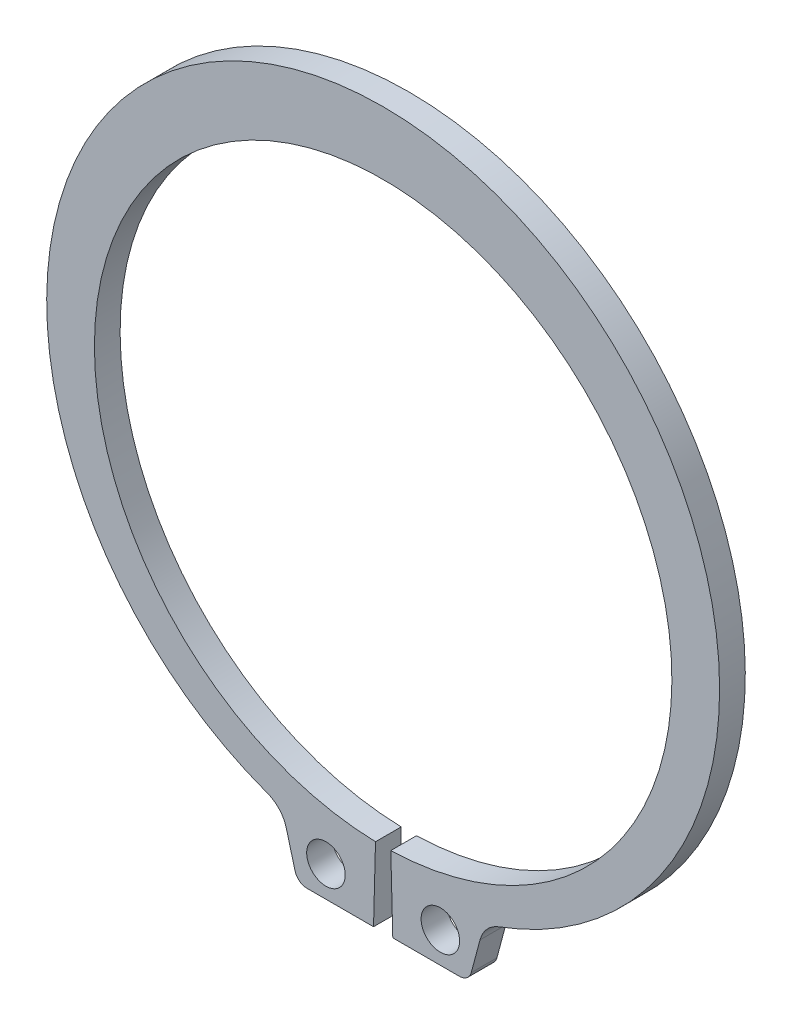
SolidWorks part; units mm, degrees
material "Alloy Steel"
ref_plane "Front" through (0, 0, 0) normal (0, 0, 1) x (1, 0, 0)
ref_plane "Top" through (0, 0, 0) normal (0, 1, 0) x (1, 0, 0)
ref_plane "Right" through (0, 0, 0) normal (1, 0, 0) x (0, 0, -1)
sketch "Sketch1" plane through (0, 0, 0) normal (0, 0, 1) x (1, 0, 0)
  line L0 (3.1662, -15.7184) -> (0.3996, -15.7184)
  line L1 (-0.3175, -12.6196) -> (-0.3996, -15.7184)
  line L2 (0, 0) -> (0, -20.2696) construction
  line L3 (0.3175, -12.6196) -> (0.3996, -15.7184)
  line L4 (-3.1662, -15.7184) -> (-0.3996, -15.7184)
  line L5 (-4.0221, -13.9789) -> (-3.6569, -15.3419)
  line L6 (4.0221, -13.9789) -> (3.6569, -15.3419)
  arc A0 (4.8114, -13.1153) -> (-4.8114, -13.1153) centre (0, 0) ccw
  arc A1 (0.3175, -12.6196) -> (-0.3175, -12.6196) centre (0, -0.635) ccw
  arc A2 (-4.8114, -13.1153) -> (-4.0221, -13.9789) centre (-5.2488, -14.3076) cw
  arc A3 (3.6569, -15.3419) -> (3.1662, -15.7184) centre (3.1662, -15.2104) cw
  arc A4 (-3.6569, -15.3419) -> (-3.1662, -15.7184) centre (-3.1662, -15.2104) ccw
  circle A5 centre (-2.3749, -14.4484) radius 0.8001
  circle A6 centre (2.3749, -14.4484) radius 0.8001
  arc A7 (4.8114, -13.1153) -> (4.0221, -13.9789) centre (5.2488, -14.3076) ccw
  point P17 (-3.556, -15.7184)
  dimension "D1" = 27.94
  dimension "D2" = 23.9776
  dimension "D4" = 1.27
  dimension "D5" = 15
  dimension "D9" = 0.508
  dimension "D12" = 1.6002
  dimension "D3" = 0.635
  dimension "D6" = 3.0988
  dimension "D7" = 0.635
  dimension "D8" = 3.556
  dimension "D10" = 4.7498
  dimension "D11" = 1.27
extrude "Boss-Extrude1" add sketch "Sketch1" along normal blind 1.0668
